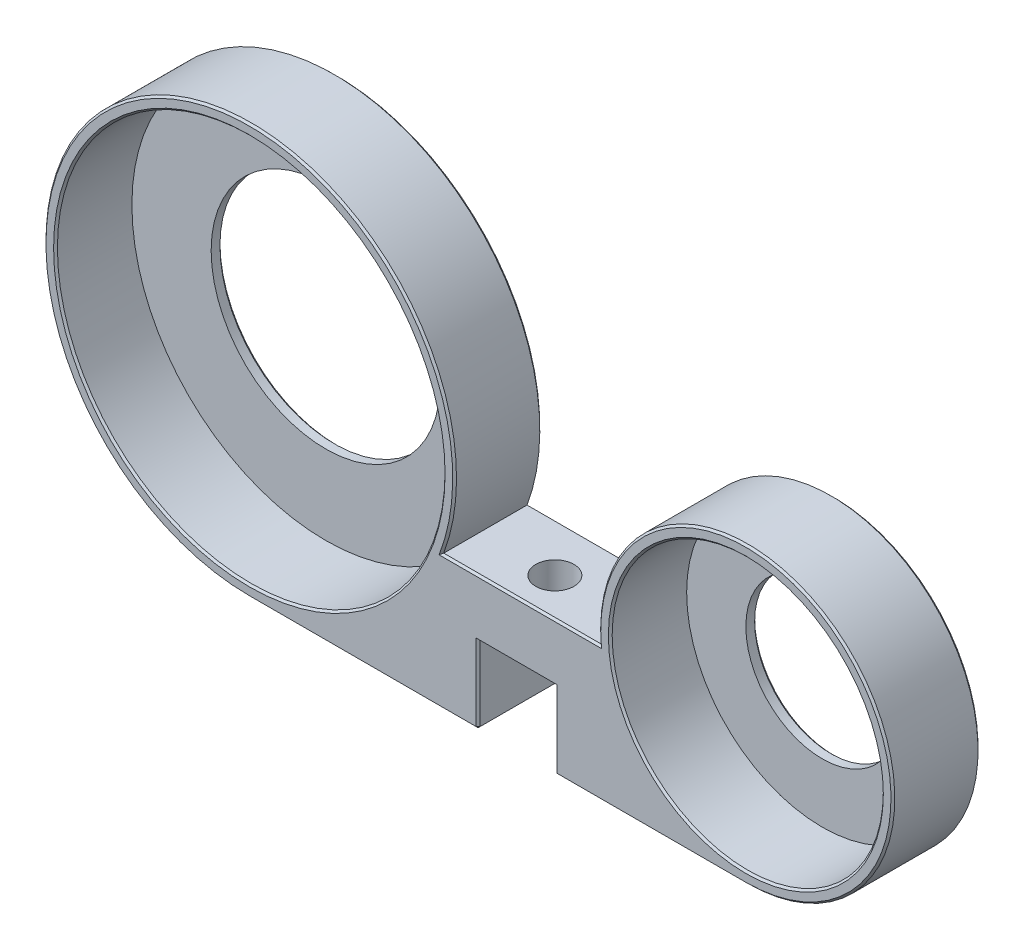
SolidWorks part; units mm, degrees
ref_plane "Front Plane" through (0, 0, 0) normal (0, 0, 1) x (1, 0, 0)
ref_plane "Top Plane" through (0, 0, 0) normal (0, 1, 0) x (1, 0, 0)
ref_plane "Right Plane" through (0, 0, 0) normal (1, 0, 0) x (0, 0, -1)
sketch "Sketch1" plane through (0, 0, 0) normal (0, 0, 1) x (1, 0, 0)
  line L0 (0, 183.4448) -> (0, -157.2487) construction
  line L1 (-201.3025, 0) -> (177.4186, 0) construction
  line L3 (-161, 10) -> (-141, 10)
  line L4 (-161, 10) -> (-161, -10)
  line L5 (-161, -10) -> (-141, -10)
  line L6 (-141, 10) -> (-141, -10)
  line L11 (-10, 129) -> (10, 129)
  line L12 (-10, 129) -> (-10, 109)
  line L13 (-10, 109) -> (10, 109)
  line L14 (10, 129) -> (10, 109)
  circle A0 centre (0, 0) radius 109
  circle A2 centre (0, 0) radius 151
  circle A3 centre (-141.9499, 51.49) radius 34.75
  circle A4 centre (-46, 143.8228) radius 34.75
  circle A5 centre (46, 143.8228) radius 34.75
  dimension "D5" = 218
  dimension "D6" = 69.5
  dimension "D7" = 302
  dimension "D11" = 69.5
  dimension "D12" = 46
  dimension "D1" = 20
  dimension "D2" = 20
  dimension "D3" = 10
  dimension "D4" = 161
  dimension "D8" = 20
  dimension "D9" = 20
  dimension "D10" = 10
sketch "Sketch2" plane through (0, 0, 0) normal (0, 0, 1) x (1, 0, 0)
  line L0 (0, 244.8729) -> (0, -227.2996) construction
  line L1 (-233.2438, 0) -> (222.4073, 0) construction
  line L3 (-10.1, 109) -> (-10.1, 129.1)
  line L4 (-10.1, 129.1) -> (10.1, 129.1)
  line L5 (-10, 109) -> (10, 109) construction
  line L7 (10.1, 109) -> (10.1, 129.1)
  line L9 (-113.021, 109) -> (128.7332, 109) construction
  line L10 (-19.5893, 144.1) -> (21.6504, 144.1)
  line L11 (-10.1, 109) -> (-70, 109)
  line L12 (10.1, 109) -> (60, 109)
  arc A4 (-19.5893, 144.1) -> (-70, 109) centre (-70, 162.75) ccw
  arc A5 (60, 109) -> (21.6504, 144.1) centre (60, 147.5) ccw
  circle A6 centre (-70, 162.75) radius 50.75
  circle A7 centre (60, 147.5) radius 35.5
  point P21 (0, 144.1)
  point P22 (0, 129.1)
  dimension "D1" = 107.5
  dimension "D2" = 53.75
  dimension "D5" = 70
  dimension "D6" = 77
  dimension "D7" = 38.5
  dimension "D8" = 60
  dimension "D9" = 101.5
  dimension "D10" = 71
  dimension "D3" = 10.1
  dimension "D4" = 20.1
  dimension "D11" = 15
  dimension "D12" = 20.1
extrude "Boss-Extrude1" add sketch "Sketch2" along normal blind 20
sketch "Sketch3" plane through (0, 0, 0) normal (0, 1, 0) x (1, 0, 0)
  line L0 (0, 50.6164) -> (0, -69.0821) construction
  circle A0 centre (0, -10) radius 2.75
  dimension "D1" = 5.5
  dimension "D2" = 10
extrude "Cut-Extrude1" cut sketch "Sketch3" along normal through all
sketch "Sketch4" plane through (0, 144.1, 0) normal (0, 1, 0) x (1, 0, 0)
  circle A0 centre (0, -10) radius 5
  dimension "D1" = 10
extrude "Cut-Extrude2" cut sketch "Sketch4" against normal blind 10
sketch "Sketch5" plane through (0, 0, 0) normal (0, 0, -1) x (-1, 0, 0)
  line L6 (10.1, 109) -> (70, 109)
  line L7 (19.5893, 144.1) -> (-21.6504, 144.1)
  line L8 (-60, 109) -> (-10.1, 109)
  line L9 (-10.1, 109) -> (-10.1, 129.1)
  line L10 (-10.1, 129.1) -> (10.1, 129.1)
  line L11 (10.1, 129.1) -> (10.1, 109)
  line L12 (10.1, 109) -> (70, 109)
  line L13 (19.5893, 144.1) -> (-21.6504, 144.1)
  line L14 (-60, 109) -> (-10.1, 109)
  line L15 (-10.1, 109) -> (-10.1, 129.1)
  line L16 (-10.1, 129.1) -> (10.1, 129.1)
  line L17 (10.1, 129.1) -> (10.1, 109)
  circle A0 centre (-60, 147.5) radius 20
  circle A1 centre (70, 162.75) radius 30
  arc A2 (70, 109) -> (19.5893, 144.1) centre (70, 162.75) ccw
  arc A3 (-21.6504, 144.1) -> (-60, 109) centre (-60, 147.5) ccw
  arc A4 (70, 109) -> (19.5893, 144.1) centre (70, 162.75) ccw
  arc A5 (-21.6504, 144.1) -> (-60, 109) centre (-60, 147.5) ccw
  dimension "D2" = 40
  dimension "D3" = 60
  dimension "D1" = 0
extrude "Boss-Extrude2" add sketch "Sketch5" along normal blind 3
chamfer "Chamfer1" distance 0.7 angle 45 10 edges at (-100, 162.75, -3) (0, 129.1, -3) (10.1, 119.05, -3) (35.05, 109, -3) (85.9937, 175.9003, -3) (1.0306, 144.1, -3) (-100.7134, 206.8607, -3) (-40.05, 109, -3) (-10.1, 119.05, -3) (40, 147.5, -3)
chamfer "Chamfer2" distance 0.5 angle 45 12 edges at (95.5, 147.5, 20) (-19.25, 162.75, 20) (-100.7134, 206.8607, 20) (1.0306, 144.1, 20) (85.9937, 175.9003, 20) (35.05, 109, 20) (-40.05, 109, 20) (-10.1, 109, 8.85) (-10.1, 119.05, 20) (0, 129.1, 20) (10.1, 119.05, 20) (10.1, 109, 8.85)
